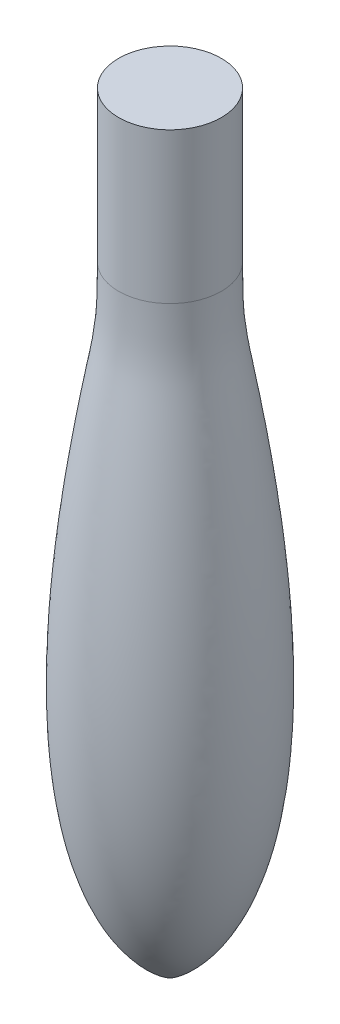
SolidWorks part; units mm, degrees
ref_plane "Front Plane" through (0, 0, 0) normal (0, 0, 1) x (1, 0, 0)
ref_plane "Top Plane" through (0, 0, 0) normal (0, 1, 0) x (1, 0, 0)
ref_plane "Right Plane" through (0, 0, 0) normal (1, 0, 0) x (0, 0, -1)
sketch "Sketch1" plane through (0, 0, 0) normal (1, 0, 0) x (0, 0, -1)
  line L0 (0, 29.3) -> (0, -120.7)
  line L1 (0, 29.3) -> (10, 29.3)
  line L2 (10, 29.3) -> (10, 0)
  line L3 (10, -11.5094) -> (10, 12.1325) construction
  spline S0 degree 3 poles (10, 0) (10, -9.375) (11.1654, -16.0996) (26.6388, -104.8414) (0, -120.7) knots 0 0 0 0 0.245942 1 1 1 1
  point P6 (0, 0)
  dimension "D1" = 10
  dimension "D2" = 150
  dimension "D3" = 29.3
revolve "Revolve1" add sketch "Sketch1" angle 360 about L0
